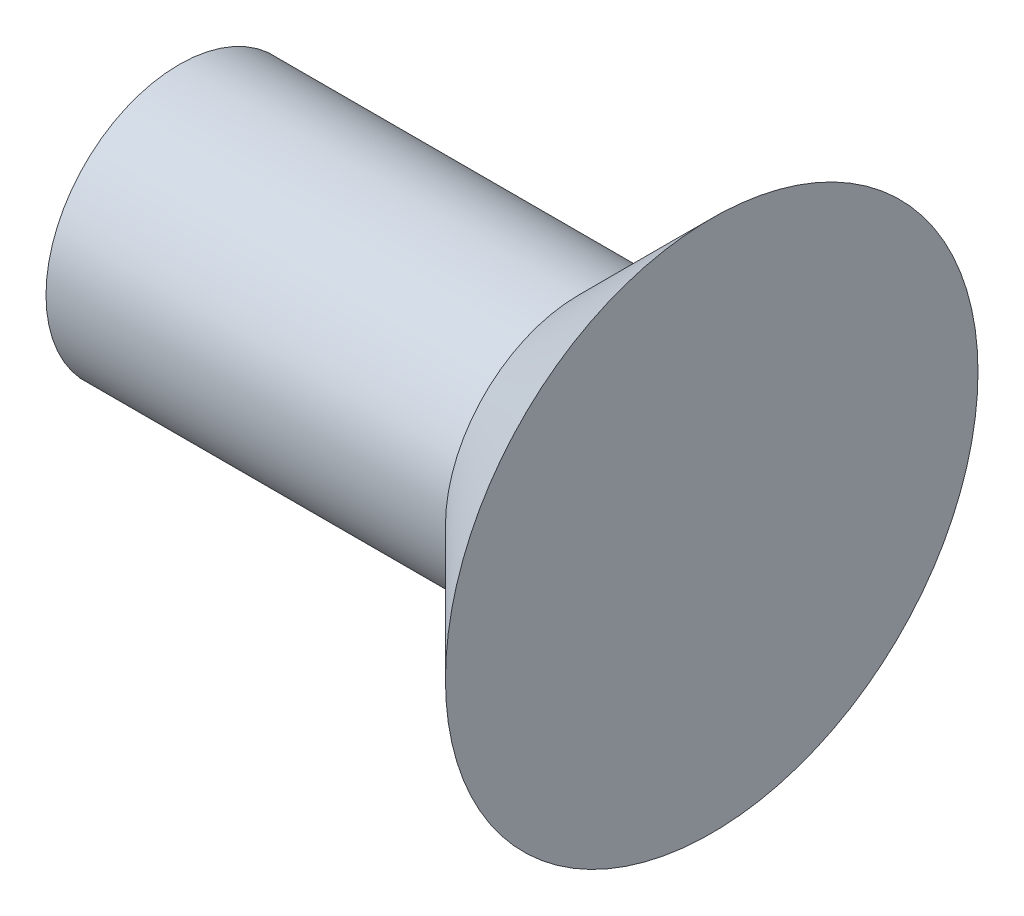
SolidWorks part; units mm, degrees
other "Preload Guide Stop M3 Bolt"
ref_plane "Front Plane" through (0, 0, 0) normal (0, 0, 1) x (1, 0, 0)
ref_plane "Top Plane" through (0, 0, 0) normal (0, 1, 0) x (1, 0, 0)
ref_plane "Right Plane" through (0, 0, 0) normal (1, 0, 0) x (0, 0, -1)
sketch3d "M3 fixing shank sketch datum points"
  point P0 (54.2, -18.5, -28)
  point P1 (54.2, -8.5, -28)
  point P2 (54.2, -18.5, -18)
ref_plane "M3 fixing shank sketch plane" through (54.2, 0, 0) normal (1, 0, 0) x (0, 0, -1)
sketch "M3 fixing shank sketch" plane through (54.2, 0, 0) normal (1, 0, 0) x (0, 0, -1)
  circle A0 centre (28, -18.5) radius 1.5
extrude "M3 fixing shank" add sketch "M3 fixing shank sketch" along normal blind 4.5 separate body
sketch3d "Countersunk screw head axis line"
  line L0 (48.7, -18.5, -28) -> (68.7, -18.5, -28) construction
ref_axis "Countersunk screw head axis" through (48.7, -18.5, -28) along (1, 0, 0)
sketch3d "Countersunk screw head profile datum points"
  point P0 (58.7, -18.5, -28)
  point P1 (58.7, -8.5, -28)
  point P2 (68.7, -18.5, -28)
ref_plane "Countersunk screw head profile plane" through (0, 0, -28) normal (0, 0, -1) x (-1, 0, 0)
sketch "Countersunk screw head profile" plane through (0, 0, -28) normal (0, 0, -1) x (-1, 0, 0)
  line L0 (-58.7, -18.5) -> (-58.7, -17)
  line L1 (-58.7, -17) -> (-60.2, -15.5)
  line L2 (-60.2, -15.5) -> (-60.2, -18.5)
  line L3 (-60.2, -18.5) -> (-58.7, -18.5)
revolve "Countersunk screw head" add sketch "Countersunk screw head profile" angle 360 about axis through (48.7, -18.5, -28) along (1, 0, 0)
